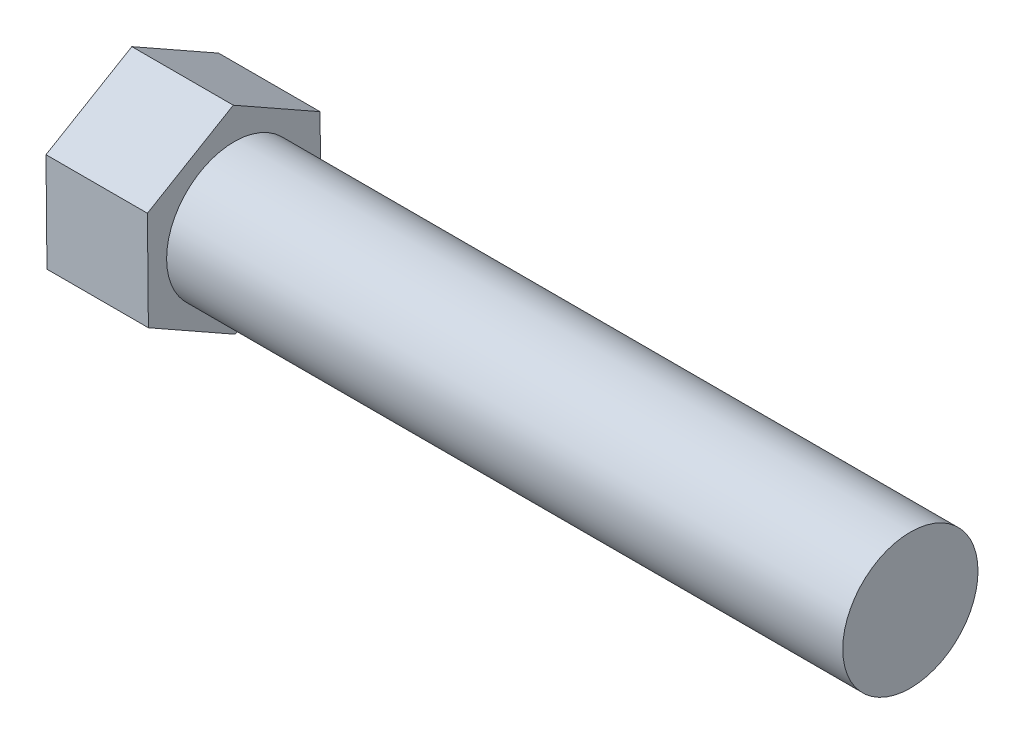
SolidWorks part; units mm, degrees
ref_plane "Спереди" through (0, 0, 0) normal (0, 0, 1) x (1, 0, 0)
ref_plane "Сверху" through (0, 0, 0) normal (0, 1, 0) x (1, 0, 0)
ref_plane "Справа" through (0, 0, 0) normal (1, 0, 0) x (0, 0, -1)
sketch "Эскиз1" plane through (0, 0, 0) normal (1, 0, 0) x (0, 0, -1)
  circle A0 centre (0, 0) radius 4
  dimension "D1" = 8
extrude "Бобышка-Вытянуть1" add sketch "Эскиз1" along normal blind 40
sketch "Эскиз2" plane through (0, 0, 0) normal (-1, 0, 0) x (0, 0, 1)
  line L1 (5.078, -2.9968) -> (5.1343, 2.8993)
  line L2 (5.1343, 2.8993) -> (0.0563, 5.8961)
  line L3 (0.0563, 5.8961) -> (-5.078, 2.9968)
  line L4 (-5.078, 2.9968) -> (-5.1343, -2.8993)
  line L5 (-5.1343, -2.8993) -> (-0.0563, -5.8961)
  line L6 (-0.0563, -5.8961) -> (5.078, -2.9968)
  circle A0 centre (0, 0) radius 5.1064 construction
extrude "Бобышка-Вытянуть2" add sketch "Эскиз2" along normal blind 6
